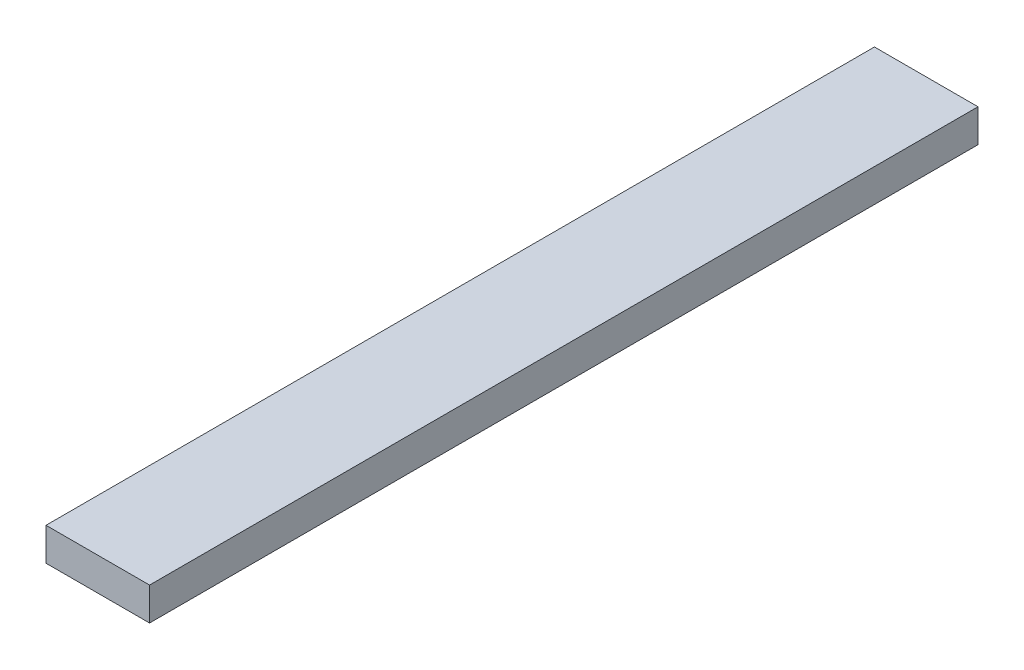
SolidWorks part; units mm, degrees
material "Acrylic (Medium-high impact)"
ref_plane "Front Plane" through (0, 0, 0) normal (0, 0, 1) x (1, 0, 0)
ref_plane "Top Plane" through (0, 0, 0) normal (0, 1, 0) x (1, 0, 0)
ref_plane "Right Plane" through (0, 0, 0) normal (1, 0, 0) x (0, 0, -1)
sketch "Sketch1" plane through (0, 0, 0) normal (0, 1, 0) x (1, 0, 0)
  line L1 (-5, -40) -> (5, -40)
  line L2 (-5, -40) -> (-5, 40)
  line L3 (-5, 40) -> (5, 40)
  line L4 (5, -40) -> (5, 40)
  line L5 (-5, -40) -> (5, 40) construction
  line L6 (-5, 40) -> (5, -40) construction
  point P0 (0, 0)
  dimension "D2" = 10
  dimension "LENGTH" = 80
extrude "Boss-Extrude1" add sketch "Sketch1" along normal blind 3.175
hole_wizard "Ø3.0mm Dowel Hole1" positions "Sketch2" profile "Sketch3" hole size "Ø3.0" standard "ANSI Metric"
sketch "Sketch2" plane through (0, 3.175, 0) normal (0, 1, 0) x (1, 0, 0)
  line L0 (5, 40) -> (-5, 40) construction
  point P0 (0, 35)
  point P2 (0, 30)
  point P7 (0, 0)
  point P8 (0, 0)
  point P9 (0, 0)
  point P10 (0, 40)
  dimension "D1" = 5
  dimension "D2" = 5
sketch "Sketch3" plane through (0, 3.175, -35) normal (1, 0, 0) x (0, 0, 1)
  line L0 (0, 0) -> (0, 3.175)
  line L1 (0, 3.175) -> (1.65, 3.175)
  line L2 (1.65, 3.175) -> (1.65, 0)
  line L5 (1.65, 0) -> (0, 0)
  line L11 (0, -6.35) -> (0, 107.95) construction
  dimension "Thru Hole Dia." = 3.3
  dimension "Thru Hole Depth" = 3.175
